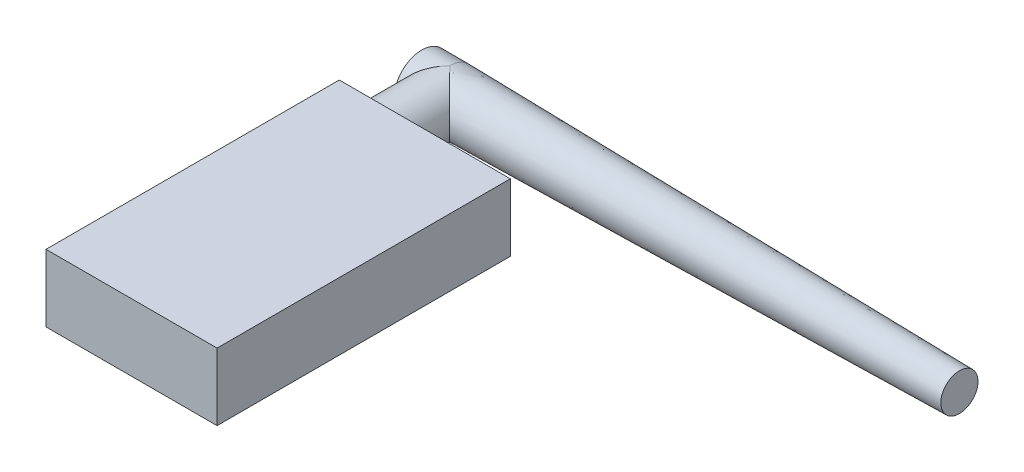
SolidWorks part; units mm, degrees
ref_plane "Piano frontale" through (0, 0, 0) normal (0, 0, 1) x (1, 0, 0)
ref_plane "Piano superiore" through (0, 0, 0) normal (0, 1, 0) x (1, 0, 0)
ref_plane "Piano destro" through (0, 0, 0) normal (1, 0, 0) x (0, 0, -1)
sketch "Schizzo1" plane through (0, 0, 0) normal (0, 1, 0) x (1, 0, 0)
  line L1 (-14, -24) -> (14, -24)
  line L2 (-14, -24) -> (-14, 24)
  line L3 (-14, 24) -> (14, 24)
  line L4 (14, -24) -> (14, 24)
  line L5 (-14, -24) -> (14, 24) construction
  line L6 (-14, 24) -> (14, -24) construction
  point P0 (0, 0)
  dimension "D1" = 48
  dimension "D2" = 28
extrude "Estrusione-Estrusione1" add sketch "Schizzo1" along normal blind 11
sketch "Schizzo3" plane through (0, 0, -24) normal (0, 0, -1) x (-1, 0, 0)
  line L1 (14, 5.5) -> (8, 5.5) construction
  line L2 (14, 11) -> (14, 0) construction
  circle A0 centre (8, 5.5) radius 4.5
  dimension "D1" = 9
  dimension "D2" = 6
extrude "Estrusione-Estrusione2" add sketch "Schizzo3" along normal blind 12
ref_plane "Piano1" through (-8, 0, 0) normal (1, 0, 0) x (0, 0, -1)
sketch "Schizzo4" plane through (-8, 0, 0) normal (1, 0, 0) x (0, 0, -1)
  line L2 (24, 11) -> (24, 0) construction
  line L4 (36, 5.5) -> (24, 5.5) construction
  line L5 (24, 1) -> (24, 10) construction
  circle A0 centre (36, 5.5) radius 4.5
  dimension "D1" = 9
  dimension "D2" = 12
extrude "Estrusione-Estrusione3" add sketch "Schizzo4" along normal blind 83.5 draft 1 and the other way blind 4.5
